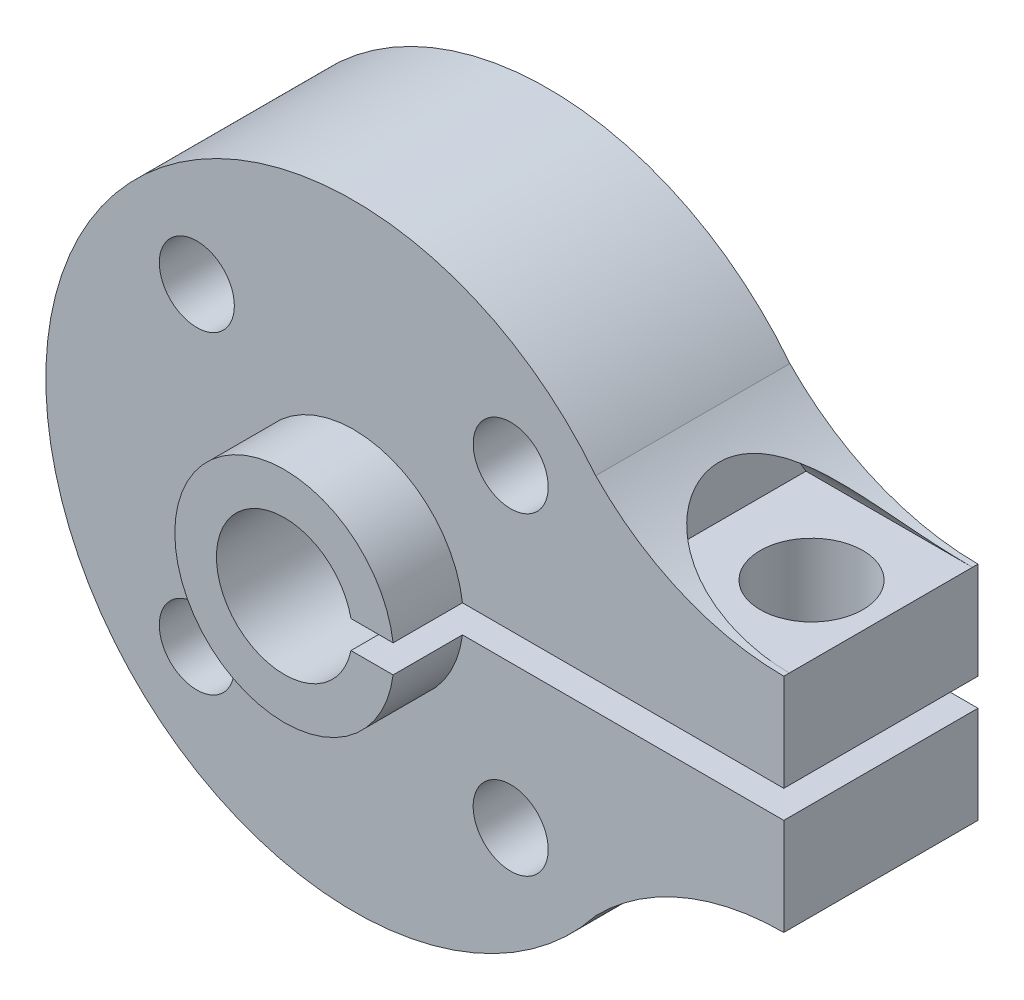
SolidWorks part; units mm, degrees
material "6061 Alloy"
ref_plane "Front Plane" through (0, 0, 0) normal (0, 0, 1) x (1, 0, 0)
ref_plane "Top Plane" through (0, 0, 0) normal (0, 1, 0) x (1, 0, 0)
ref_plane "Right Plane" through (0, 0, 0) normal (1, 0, 0) x (0, 0, -1)
sketch "Sketch1" plane through (0, 0, 0) normal (0, 0, 1) x (1, 0, 0)
  line L0 (-18.136, 0) -> (24.0528, 0) construction
  line L1 (0, 0) -> (0, 0.5)
  line L2 (0, 0.5) -> (15.5, 0.5)
  line L3 (15.5, 0.5) -> (15.5, 4)
  line L5 (0, 0) -> (0, -0.5)
  line L6 (0, -0.5) -> (15.5, -0.5)
  line L7 (15.5, -0.5) -> (15.5, -4)
  arc A0 (8.7199, 6.8683) -> (8.7199, -6.8683) centre (0, 0) ccw
  arc A6 (15.5, 4) -> (8.7199, 6.8683) centre (15.5, 13.4476) cw
  arc A7 (15.5, -4) -> (8.7199, -6.8683) centre (15.5, -13.4476) ccw
  dimension "D1" = 22.2
  dimension "D3" = 0.5
  dimension "D4" = 0.5
  dimension "D5" = 3.5
  dimension "D6" = 3.5
  dimension "D7" = 15.5
  dimension "D8" = 15.5
extrude "Extrude1" add sketch "Sketch1" against normal blind 7
sketch "Sketch2" plane through (0, 0, 0) normal (0, 0, 1) x (1, 0, 0)
  circle A1 centre (5.6572, 5.6565) radius 1.85
  circle A2 centre (-5.6572, -5.6565) radius 1.85
  circle A3 centre (5.6565, -5.6572) radius 1.85
  circle A4 centre (-5.6565, 5.6572) radius 1.85
hole_wizard "#6-32 Tapped Hole3" positions "3DSketch3" profile "Sketch5" tap size "#6-32" standard "Ansi Inch" end condition through all
sketch3d "3DSketch3"
  point P0 (-5.6565, 5.6572, 0)
  point P3 (5.6572, 5.6565, 0)
  point P6 (5.6565, -5.6572, 0)
  point P9 (-5.6572, -5.6565, 0)
sketch "Sketch5" plane through (-5.6565, 5.6572, 0) normal (1, 0, 0) x (0, -1, 0)
  line L0 (0, 0) -> (0, 7)
  line L1 (0, 7) -> (1.3525, 7)
  line L2 (1.3525, 7) -> (1.3525, 0)
  line L5 (1.3525, 0) -> (0, 0)
  line L11 (0, -6.35) -> (0, 107.95) construction
  dimension "Thru Tap Drill Dia." = 2.7051
  dimension "Thru Tap Drill Depth" = 7
cosmetic thread "Hole Thread4" parameters "D2"=3.5052
cosmetic thread "Hole Thread5" parameters "D2"=3.5052
cosmetic thread "Hole Thread6" parameters "D2"=3.5052
cosmetic thread "Hole Thread7" parameters "D2"=3.5052
sketch "Sketch8" plane through (0, 0, 0) normal (0, 0, 1) x (1, 0, 0)
  line L0 (3.9182, -0.5) -> (0, -0.5)
  line L1 (15.5, -0.5) -> (0, -0.5) construction
  line L2 (0, -0.5) -> (0, 0.5)
  line L3 (0, 0.5) -> (3.9182, 0.5)
  line L4 (0, 0.5) -> (15.5, 0.5) construction
  arc A0 (3.9182, 0.5) -> (3.9182, -0.5) centre (0, 0) ccw
  dimension "D1" = 7.9
extrude "Extrude3" add sketch "Sketch8" along normal blind 2.5
sketch "Sketch9" plane through (0, 0, 2.5) normal (0, 0, 1) x (1, 0, 0)
  circle A0 centre (0, 0) radius 2.45
  dimension "D1" = 4.9
extrude "Cut-Extrude3" cut sketch "Sketch9" against normal through all
sketch "Sketch14" plane through (0, 0.5, 0) normal (0, -1, 0) x (1, 0, 0)
  line L0 (15.5, -7) -> (15.5, 0) construction
  circle A0 centre (13, -3.5) radius 1.85
  dimension "D1" = 3.7
  dimension "D2" = 2.5
extrude "Cut-Extrude6" cut sketch "Sketch14" against normal through all
hole_wizard "#6-32 Tapped Hole5" positions "Sketch19" profile "Sketch18" tap size "#6-32" standard "Ansi Inch"
sketch "Sketch19" plane through (0, -0.5, 0) normal (0, 1, 0) x (-1, 0, 0)
  line L0 (-15.5, -7) -> (-15.5, 0) construction
  point P0 (-13, -3.5)
  dimension "D1" = 2.5
sketch "Sketch18" plane through (13, -0.5, -3.5) normal (1, 0, 0) x (0, 0, 1)
  line L0 (0, 0) -> (0, 51.6127)
  line L1 (0, 51.6127) -> (1.3525, 50.8)
  line L2 (1.3525, 50.8) -> (1.3525, 0)
  line L5 (1.3525, 0) -> (0, 0)
  line L10 (0, 51.6127) -> (-1.3526, 50.8) construction
  line L11 (0, -6.35) -> (0, 107.95) construction
  dimension "Tap Drill Dia." = 2.7051
  dimension "Tap Drill Depth" = 50.8
  dimension "Drill Angle" = 118
cosmetic thread "Hole Thread10" parameters "D1"=4.3212, "D2"=3.5052
sketch "Sketch24" plane through (15.5, 0, 0) normal (1, 0, 0) x (0, 0, -1)
  line L1 (7, 4) -> (0, 4) construction
  line L2 (0.2, 4) -> (6.8, 4)
  arc A0 (0.2, 4) -> (6.8, 4) centre (3.5, 2.3082) cw
  dimension "D1" = 0.2
  dimension "D2" = 0.2
extrude "Cut-Extrude26" cut sketch "Sketch24" against normal blind 6
